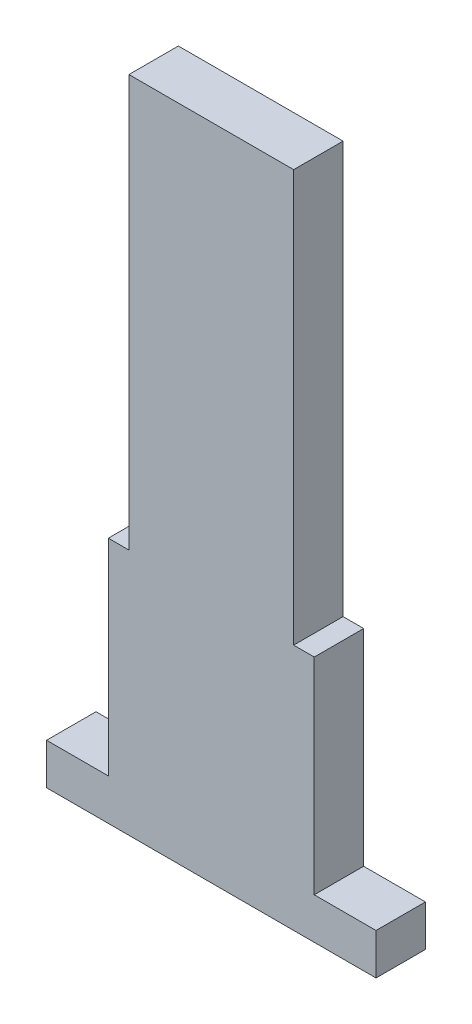
SolidWorks part; units mm, degrees
ref_plane "Front Plane" through (0, 0, 0) normal (0, 0, 1) x (1, 0, 0)
ref_plane "Top Plane" through (0, 0, 0) normal (0, 1, 0) x (1, 0, 0)
ref_plane "Right Plane" through (0, 0, 0) normal (1, 0, 0) x (0, 0, -1)
sketch "Sketch1" plane through (0, 0, 0) normal (0, 0, 1) x (1, 0, 0)
  line L0 (55, 0) -> (-55, 0) construction
  line L2 (-2.5, 0) -> (-2.5, 5)
  line L3 (-2.5, 5) -> (-2, 5)
  line L4 (2.5, 0) -> (2.5, 5)
  line L5 (-2, 15) -> (2, 5) construction
  line L7 (2, 5) -> (2, 15)
  line L8 (2, 15) -> (-2, 15)
  line L9 (-2, 5) -> (-2, 15)
  line L10 (2.5, 5) -> (-2.5, 0) construction
  line L11 (0, -55) -> (0, 55) construction
  line L12 (2, 5) -> (2.5, 5)
  line L13 (-4, 0) -> (4, -1) construction
  line L14 (-4, 0) -> (-2.5, 0)
  line L15 (-4, 0) -> (-4, -1)
  line L16 (-4, -1) -> (4, -1)
  line L17 (4, 0) -> (4, -1)
  line L18 (2.5, 0) -> (4, 0)
  point P10 (0, 2.5)
  point P13 (0, 10)
  point P18 (0, -0.5)
  dimension "D1" = 4
  dimension "D2" = 5
  dimension "D3" = 5
  dimension "D4" = 10
  dimension "D5" = 1
  dimension "D6" = 8
extrude "Boss-Extrude1" add sketch "Sketch1" along normal mid plane 1.2
